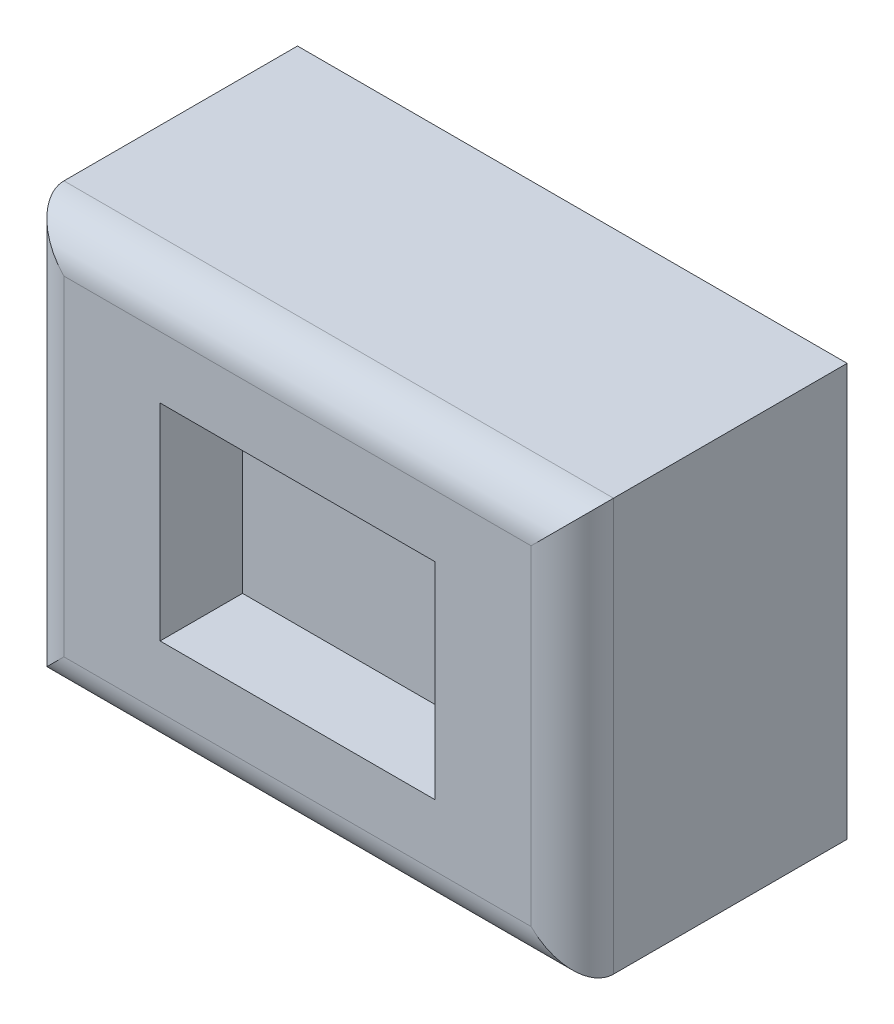
SolidWorks part; units mm, degrees
ref_plane "正面" through (0, 0, 0) normal (0, 0, 1) x (1, 0, 0)
ref_plane "平面" through (0, 0, 0) normal (0, 1, 0) x (1, 0, 0)
ref_plane "右側面" through (0, 0, 0) normal (1, 0, 0) x (0, 0, -1)
sketch "ｽｹｯﾁ1" plane through (0, 0, 0) normal (0, 0, 1) x (1, 0, 0)
  line L1 (-20, -15) -> (20, -15)
  line L2 (-20, -15) -> (-20, 15)
  line L3 (-20, 15) -> (20, 15)
  line L4 (20, -15) -> (20, 15)
extrude "M0_Boss" add sketch "ｽｹｯﾁ1" along normal blind 20
sketch "ｽｹｯﾁ2" plane through (0, 0, 20) normal (0, 0, 1) x (1, 0, 0)
  line L1 (-10, -7.5) -> (10, -7.5)
  line L2 (-10, -7.5) -> (-10, 7.5)
  line L3 (-10, 7.5) -> (10, 7.5)
  line L4 (10, -7.5) -> (10, 7.5)
extrude "M0_Pocket" cut sketch "ｽｹｯﾁ2" against normal blind 6
fillet "M0_TopR3" radius 3 4 edges at (-20, 0, 20) (0, -15, 20) (20, 0, 20) (0, 15, 20)
